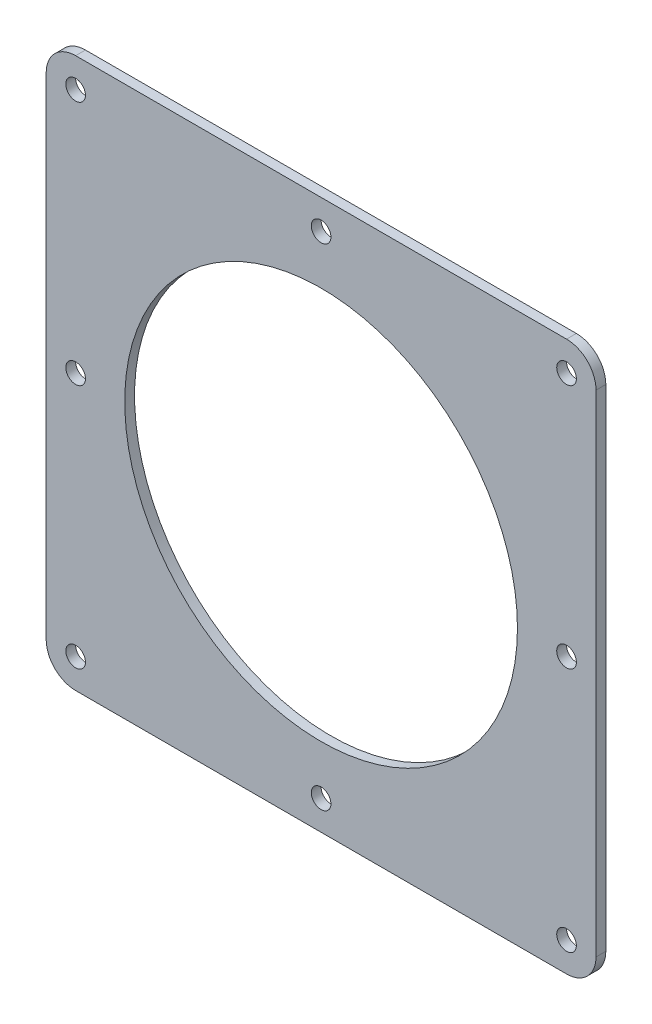
SolidWorks part; units mm, degrees
ref_plane "Front Plane" through (0, 0, 0) normal (0, 0, 1) x (1, 0, 0)
ref_plane "Top Plane" through (0, 0, 0) normal (0, 1, 0) x (1, 0, 0)
ref_plane "Right Plane" through (0, 0, 0) normal (1, 0, 0) x (0, 0, -1)
sketch "Sketch2" plane through (0, 0, 0) normal (0, 0, 1) x (1, 0, 0)
  line L0 (-125, 125) -> (125, 125) construction
  line L1 (-125, 140) -> (125, 140)
  line L2 (-140, 125) -> (-140, -125)
  line L3 (-125, -140) -> (125, -140)
  line L4 (140, 125) -> (140, -125)
  line L5 (-140, 140) -> (140, -140) construction
  line L6 (-140, -140) -> (140, 140) construction
  line L7 (125, 125) -> (125, -125) construction
  line L8 (125, -125) -> (-125, -125) construction
  line L9 (-125, -125) -> (-125, 125) construction
  arc A0 (-140, -125) -> (-125, -140) centre (-125, -125) ccw
  arc A1 (125, -140) -> (140, -125) centre (125, -125) ccw
  arc A2 (125, 140) -> (140, 125) centre (125, 125) cw
  arc A3 (-125, 140) -> (-140, 125) centre (-125, 125) ccw
  circle A4 centre (-125, 125) radius 5
  circle A5 centre (0, 125) radius 5
  circle A6 centre (125, 125) radius 5
  circle A13 centre (0, 0) radius 4
  circle A14 centre (125, 0) radius 5
  circle A15 centre (-125, 0) radius 5
  circle A16 centre (-125, -125) radius 5
  circle A17 centre (0, -125) radius 5
  circle A18 centre (125, -125) radius 5
  point P0 (0, 0)
  dimension "D3" = 15
  dimension "D4" = 10
  dimension "D5" = 10
  dimension "D6" = 10
  dimension "D7" = 8
  dimension "D8" = 10
  dimension "D9" = 10
  dimension "D10" = 10
  dimension "D11" = 10
  dimension "D1" = 280
  dimension "D2" = 280
extrude "Boss-Extrude1" add sketch "Sketch2" along normal blind 5
sketch "Sketch7" plane through (0, 0, 5) normal (0, 0, 1) x (1, 0, 0)
  circle A0 centre (0, 0) radius 100
  dimension "D1" = 200
extrude "Cut-Extrude2" cut sketch "Sketch7" against normal blind 10
